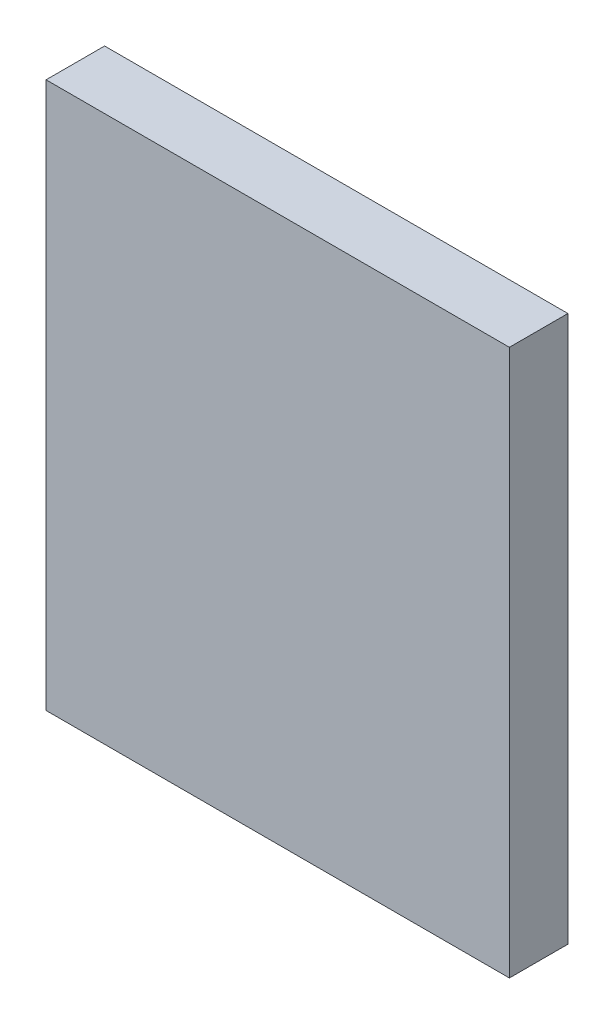
SolidWorks part; units mm, degrees
material "Glass"
ref_plane "Front Plane" through (0, 0, 0) normal (0, 0, 1) x (1, 0, 0)
ref_plane "Top Plane" through (0, 0, 0) normal (0, 1, 0) x (1, 0, 0)
ref_plane "Right Plane" through (0, 0, 0) normal (1, 0, 0) x (0, 0, -1)
sketch "Sketch1" plane through (0, 0, 0) normal (0, 0, 1) x (1, 0, 0)
  line L1 (0, 0) -> (9.5, 0)
  line L2 (0, 0) -> (0, 11.2)
  line L3 (0, 11.2) -> (9.5, 11.2)
  line L4 (9.5, 0) -> (9.5, 11.2)
  dimension "D1" = 9.5
  dimension "D2" = 11.2
extrude "Boss-Extrude1" add sketch "Sketch1" along normal blind 1.2
